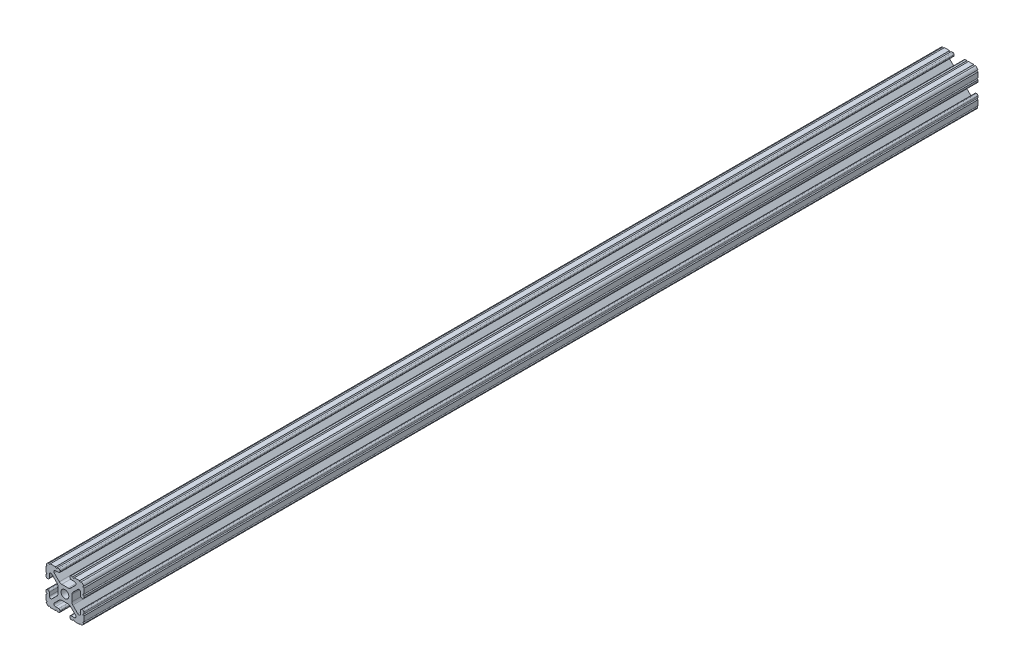
SolidWorks part; units mm, degrees
ref_plane "Front Plane" through (0, 0, 0) normal (0, 0, 1) x (1, 0, 0)
ref_plane "Top Plane" through (0, 0, 0) normal (0, 1, 0) x (1, 0, 0)
ref_plane "Right Plane" through (0, 0, 0) normal (1, 0, 0) x (0, 0, -1)
sketch "Sketch2" plane through (0, 0, 0) normal (0, 0, 1) x (1, 0, 0)
  line L0 (0, 12.7) -> (0, -12.7) construction
  line L1 (-12.7, 0) -> (12.7, 0) construction
  line L2 (3.2512, -12.7) -> (12.7, -12.7)
  line L3 (12.7, -12.7) -> (12.7, -3.2512)
  line L4 (3.2512, -12.7) -> (3.2512, -10.4902)
  line L5 (3.2512, -10.4902) -> (8.9276, -10.4902)
  line L6 (8.9276, -10.4902) -> (3.0856, -4.6482)
  line L7 (0, 0) -> (12.7, -12.7) construction
  line L8 (12.7, -3.2512) -> (10.4902, -3.2512)
  line L9 (10.4902, -3.2512) -> (10.4902, -8.9276)
  line L10 (10.4902, -8.9276) -> (4.6482, -3.0856)
  circle A0 centre (0, 0) radius 2.6035
  arc A1 (6.3485, -10.4902) -> (7.1039, -8.6665) centre (6.3485, -9.4219) ccw construction
  point P8 (0, -4.6482)
  dimension "Center Hole Diameter" = 5.207
  dimension "Rail Height" = 25.4
  dimension "Rail Width" = 25.4
  dimension "T-Slot Width" = 6.5024
  dimension "Slot Inner Width" = 14.8336
  dimension "Thickness" = 2.2098
  dimension "Slot Depth" = 5.842
  dimension "D1" = 2.2098
sketch "Sketch3" plane through (0, 0, 0) normal (1, 0, 0) x (0, 0, -1)
  line L0 (-300, -12.7) -> (300, -12.7) construction
  line L1 (-274.6, 0) -> (274.6, 0) construction
  dimension "Length" = 600
  dimension "D1" = 25.4
sketch "Sketch4" plane through (0, 0, 0) normal (0, 0, 1) x (1, 0, 0)
  line L0 (4.1904, -12.7) -> (10.1173, -12.7)
  line L1 (3.2512, -12.7) -> (12.7, -12.7) construction
  line L2 (3.2512, -12.7) -> (3.2512, -10.4902) construction
  line L3 (3.2512, -10.4902) -> (8.9276, -10.4902) construction
  line L4 (3.2512, -11.4294) -> (3.2512, -11.7608)
  line L5 (4.1904, -10.4902) -> (6.3485, -10.4902)
  line L6 (0, -4.6482) -> (2.164, -4.6482)
  line L7 (8.9276, -10.4902) -> (3.0856, -4.6482) construction
  line L8 (3.7373, -5.2999) -> (7.1039, -8.6665)
  line L9 (12.7, -12.7) -> (12.7, -3.2512) construction
  line L10 (10.4902, -8.9276) -> (4.6482, -3.0856) construction
  line L11 (10.4902, -3.2512) -> (10.4902, -8.9276) construction
  line L12 (10.4902, -6.3485) -> (10.4902, -4.1904)
  line L13 (12.7, -3.2512) -> (10.4902, -3.2512) construction
  line L14 (11.4294, -3.2512) -> (11.7608, -3.2512)
  line L15 (12.7, -4.1904) -> (12.7, -10.1173)
  line L16 (8.6665, -7.1039) -> (5.2999, -3.7373)
  line L17 (4.6482, 0) -> (4.6482, -2.164)
  line L18 (-12.7, 0) -> (12.7, 0) construction
  line L19 (0, -4.6482) -> (0, -2.6035)
  line L20 (0, 12.7) -> (0, -12.7) construction
  line L21 (4.6482, 0) -> (2.6035, 0)
  arc A0 (3.2512, -11.7608) -> (4.1904, -12.7) centre (4.1904, -11.7608) ccw
  arc A2 (3.2512, -11.4294) -> (4.1904, -10.4902) centre (4.1904, -11.4294) cw
  arc A3 (6.3485, -10.4902) -> (7.1039, -8.6665) centre (6.3485, -9.4219) ccw
  arc A4 (2.164, -4.6482) -> (3.7373, -5.2999) centre (2.164, -6.8732) cw
  arc A5 (10.1173, -12.7) -> (12.7, -10.1173) centre (10.1173, -10.1173) ccw
  arc A6 (8.6665, -7.1039) -> (10.4902, -6.3485) centre (9.4219, -6.3485) ccw
  arc A7 (10.4902, -4.1904) -> (11.4294, -3.2512) centre (11.4294, -4.1904) cw
  arc A8 (11.7608, -3.2512) -> (12.7, -4.1904) centre (11.7608, -4.1904) cw
  arc A9 (5.2999, -3.7373) -> (4.6482, -2.164) centre (6.8732, -2.164) cw
  circle A10 centre (0, 0) radius 2.6035 construction
  arc A11 (0, -2.6035) -> (2.6035, 0) centre (0, 0) ccw
  dimension "D1" = 2.5827
  dimension "D2" = 2.225
  dimension "D3" = 0.9392
extrude "Boss-Extrude1" add sketch "Sketch4" along normal mid plane 600
sketch "Sketch5" plane through (0, 0, 0) normal (0, 0, 1) x (1, 0, 0)
  line L0 (3.2512, -12.7) -> (12.7, -12.7) construction
  line L1 (4.1904, -10.4902) -> (6.3485, -10.4902) construction
  line L3 (0, 0) -> (12.7, -12.7) construction
  line L4 (6.3485, -10.4902) -> (6.3485, -12.7) construction
  line L5 (8.9276, -10.4902) -> (3.0856, -4.6482) construction
  circle A0 centre (10.3562, -12.7) radius 0.5524
  circle A1 centre (5.796, -12.7) radius 0.5524
  circle A2 centre (12.7, -10.3562) radius 0.5524
  circle A3 centre (12.7, -5.796) radius 0.5524
  point P10 (5.2694, -10.4902)
  point P12 (9.4219, -6.3485)
  dimension "D1" = 1.1049
extrude "Cut-Extrude1" cut sketch "Sketch5" against normal through all both and the other way through all
mirror "Mirror1" about plane through (0, 0, 0) normal (1, 0, 0) of bodies 137 134
mirror "Mirror2" about plane through (0, 0, 0) normal (0, 1, 0) of bodies 135
sketch "Sketch6" plane through (0, 0, 0) normal (0, 1, 0) x (1, 0, 0)
  line L0 (0, -250) -> (0, 250) construction
  line L1 (0, -125) -> (0, 125) construction
  point P4 (0, 0)
  point P8 (0, 0)
  dimension "D1" = 250
  dimension "D2" = 500
ref_plane "Plane1" through (0, 0, -250) normal (0, 0, 1) x (1, 0, 0)
ref_plane "Plane2" through (0, 0, -125) normal (0, 0, 1) x (1, 0, 0)
ref_plane "Plane3" through (0, 0, 125) normal (0, 0, 1) x (1, 0, 0)
ref_plane "Plane4" through (0, 0, 250) normal (0, 0, 1) x (1, 0, 0)
equation "\"D1@Boss-Extrude1\"=\"Length@Sketch3\""
equation "\"D1@Sketch2\"=\"Thickness@Sketch2\""
equation "\"D2@Sketch4\"=\"Slot Inner Width@Sketch2\"*0.15"
equation "\"D1@Sketch4\"=\"D3@Sketch4\"*2.75"
equation "\"D3@Sketch4\"=\"Thickness@Sketch2\"*0.425"
equation "\"D1@Sketch5\"=\"Thickness@Sketch2\"*0.5"
